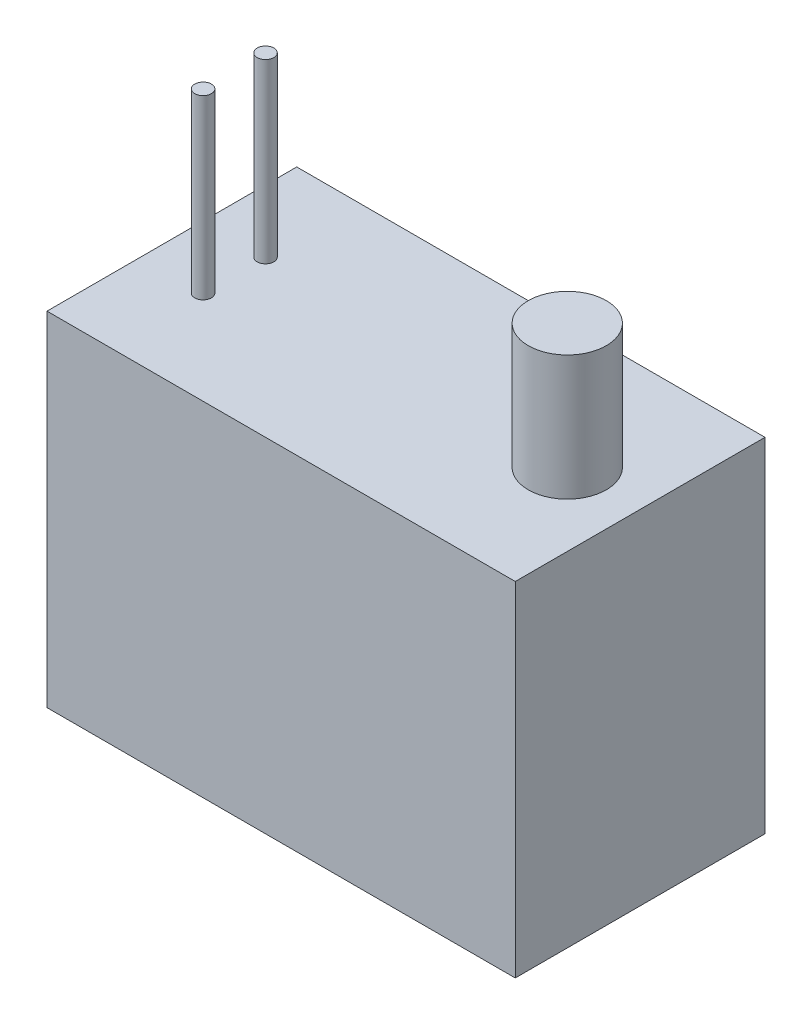
SolidWorks part; units mm, degrees
ref_plane "Front Plane" through (0, 0, 0) normal (0, 0, 1) x (1, 0, 0)
ref_plane "Top Plane" through (0, 0, 0) normal (0, 1, 0) x (1, 0, 0)
ref_plane "Right Plane" through (0, 0, 0) normal (1, 0, 0) x (0, 0, -1)
sketch "SK Pump body" plane through (0, 0, 0) normal (0, 1, 0) x (1, 0, 0)
  line L1 (0, 24) -> (45, 24)
  line L2 (0, 24) -> (0, 0)
  line L3 (0, 0) -> (45, 0)
  line L4 (45, 24) -> (45, 0)
extrude "Pump body" add sketch "SK Pump body" along normal blind 33 separate body
sketch "SK Outlet nozzle" plane through (0, 0, 0) normal (0, 1, 0) x (1, 0, 0)
  circle A0 centre (38, 12) radius 3.75
extrude "Outlet nozzle" add sketch "SK Outlet nozzle" along normal blind 12 from offset 33 separate body
sketch "SK Inlet" plane through (0, 0, 0) normal (1, 0, 0) x (0, 0, -1)
  circle A0 centre (12, 9) radius 4
extrude "Inlet" add sketch "SK Inlet" along normal blind 2 from offset 2 separate body
sketch "SK Lead red" plane through (0, 0, 0) normal (0, 1, 0) x (1, 0, 0)
  circle A0 centre (6, 9) radius 0.8
extrude "Lead red" add sketch "SK Lead red" along normal blind 17 from offset 33 separate body
sketch "SK Lead black" plane through (0, 0, 0) normal (0, 1, 0) x (1, 0, 0)
  circle A0 centre (6, 15) radius 0.8
extrude "Lead black" add sketch "SK Lead black" along normal blind 17 from offset 33 separate body
